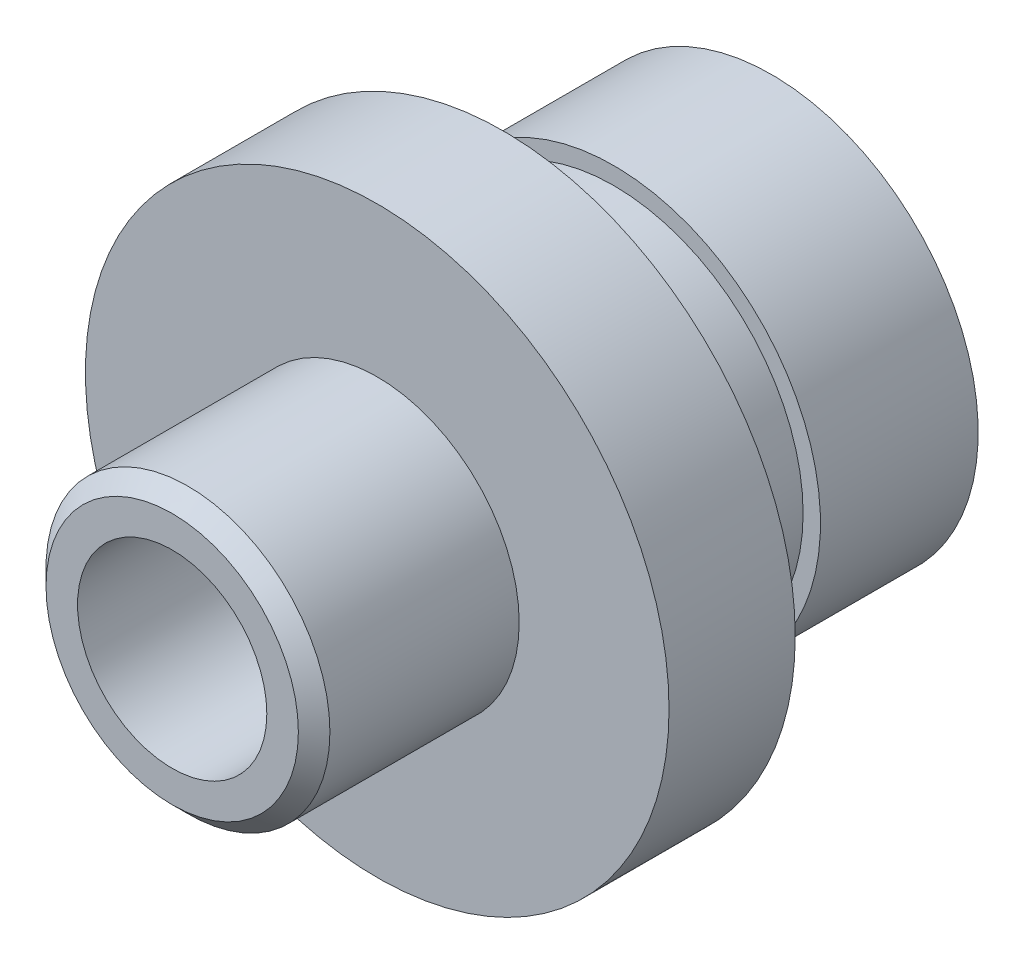
SolidWorks part; units mm, degrees
ref_plane "Front Plane" through (0, 0, 0) normal (0, 0, 1) x (1, 0, 0)
ref_plane "Top Plane" through (0, 0, 0) normal (0, 1, 0) x (1, 0, 0)
ref_plane "Right Plane" through (0, 0, 0) normal (1, 0, 0) x (0, 0, -1)
sketch "Sketch1" plane through (0, 0, 0) normal (0, 0, 1) x (1, 0, 0)
  circle A0 centre (0, 0) radius 3
  circle A1 centre (0, 0) radius 9.25
extrude "Boss-Extrude1" add sketch "Sketch1" along normal blind 19
sketch "Sketch2" plane through (0, 0, 19) normal (0, 0, 1) x (1, 0, 0)
  circle A0 centre (0, 0) radius 4.5
extrude "Cut-Extrude1" cut sketch "Sketch2" against normal blind 6.5 flip side to cut
sketch "Sketch3" plane through (0, 0, 0) normal (0, 0, -1) x (-1, 0, 0)
  circle A0 centre (0, 0) radius 6.8
extrude "Cut-Extrude2" cut sketch "Sketch3" against normal offset from surface (8.5 mm away) 4 flip side to cut up to face at (4.5, 0, 12.5)
sketch "Sketch4" plane through (0, 0, 0) normal (0, 0, -1) x (-1, 0, 0)
  circle A0 centre (0, 0) radius 6.55
extrude "Cut-Extrude3" cut sketch "Sketch4" against normal offset from surface (7 mm away) 1.5 flip side to cut up to face at (6.8, 0, 8.5)
chamfer "Chamfer1" distance 0.5 angle 45 1 edges at (4.5, 0, 19)
sketch "Sketch5" plane through (0, 0, 0) normal (0, 0, -1) x (-1, 0, 0)
  circle A0 centre (0, 0) radius 6
extrude "Cut-Extrude4" cut sketch "Sketch5" against normal blind 2 from offset 5 flip side to cut
